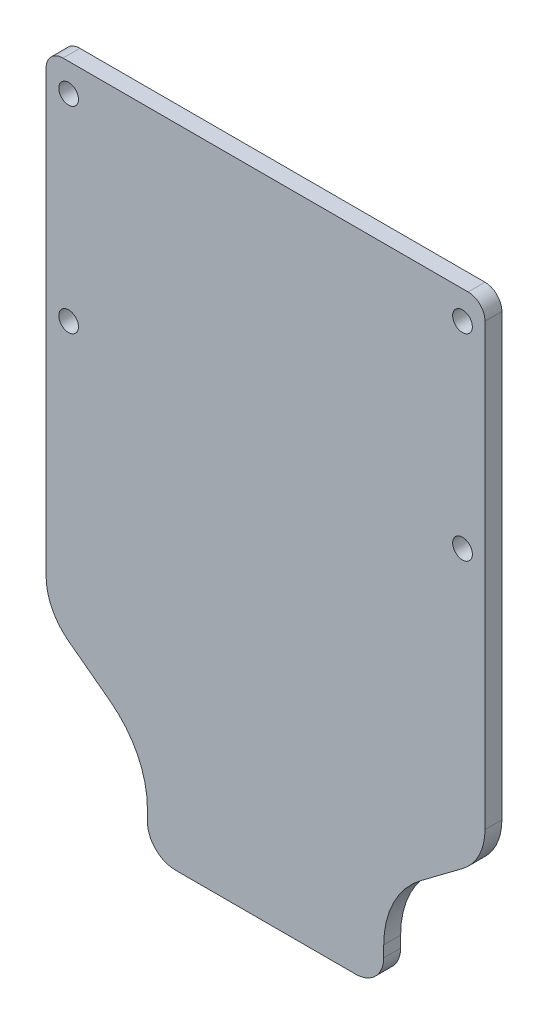
SolidWorks part; units mm, degrees
ref_plane "Front Plane" through (0, 0, 0) normal (0, 0, 1) x (1, 0, 0)
ref_plane "Top Plane" through (0, 0, 0) normal (0, 1, 0) x (1, 0, 0)
ref_plane "Right Plane" through (0, 0, 0) normal (1, 0, 0) x (0, 0, -1)
sketch "Sketch1" plane through (0, 0, 0) normal (0, 0, 1) x (1, 0, 0)
  line L1 (-35, -17.5) -> (35, -17.5) construction
  line L2 (-35, -17.5) -> (-35, 17.5) construction
  line L3 (-35, 17.5) -> (35, 17.5) construction
  line L4 (35, -17.5) -> (35, 17.5) construction
  line L5 (-35, -17.5) -> (35, 17.5) construction
  line L6 (-35, 17.5) -> (35, -17.5) construction
  line L7 (39, -22.5) -> (-39, -22.5)
  line L8 (39, -22.5) -> (39, 22.5)
  line L9 (39, 22.5) -> (-39, 22.5)
  line L10 (-39, -22.5) -> (-39, 22.5)
  line L11 (39, -22.5) -> (-39, 22.5) construction
  line L12 (39, 22.5) -> (-39, -22.5) construction
  circle A0 centre (-35, 17.5) radius 1.75
  circle A1 centre (35, 17.5) radius 1.75
  circle A2 centre (35, -17.5) radius 1.75
  circle A3 centre (-35, -17.5) radius 1.75
  point P0 (0, 0)
  point P10 (0, 0)
  dimension "D3" = 3.5
  dimension "D1" = 70
  dimension "D2" = 35
  dimension "D4" = 78
  dimension "D5" = 45
extrude "Boss-Extrude1" add sketch "Sketch1" along normal blind 3
sketch "Sketch2" plane through (0, -22.5, 0) normal (0, -1, 0) x (1, 0, 0)
  line L4 (-39, 0) -> (39, 0)
  line L5 (39, 0) -> (39, 3)
  line L6 (39, 3) -> (-39, 3)
  line L7 (-39, 3) -> (-39, 0)
  line L8 (-39, 0) -> (39, 0)
  line L9 (39, 0) -> (39, 3)
  line L10 (39, 3) -> (-39, 3)
  line L11 (-39, 3) -> (-39, 0)
  dimension "D1" = 0
extrude "Boss-Extrude2" add sketch "Sketch2" along normal blind 70
sketch "Sketch3" plane through (0, 0, 3) normal (0, 0, 1) x (1, 0, 0)
  line L0 (41, -36.9246) -> (91.4695, -36.9246)
  line L1 (91.4695, -36.9246) -> (78.5429, -118.6496)
  line L2 (78.5429, -118.6496) -> (-67.027, -120.2552)
  line L3 (-67.027, -120.2552) -> (-84.5097, -42.4751)
  line L4 (-84.5097, -42.4751) -> (-81.6554, -36.9246)
  line L5 (-81.6554, -36.9246) -> (-41, -36.9246)
  line L12 (41, -55.5) -> (41, -36.9246)
  line L13 (41, -36.9246) -> (39.1575, -36.9246)
  line L14 (25.5, -28.5324) -> (25.5, 16.1465)
  line L15 (25.5, 16.1465) -> (-25.5, 16.1465)
  line L16 (-25.5, 16.1465) -> (-25.5, -28.5324)
  line L17 (-39.1575, -36.9246) -> (-41, -36.9246)
  line L18 (-41, -36.9246) -> (-41, -55.5)
  line L19 (-35.6, -66.3) -> (-27.6, -72.3)
  line L20 (-21, -85.5) -> (-21, -101)
  line L21 (-15.5, -106.5) -> (15.5, -106.5)
  line L22 (21, -101) -> (21, -85.5)
  line L23 (27.6, -72.3) -> (35.6, -66.3)
  line L24 (41, -55.5) -> (41, -36.9246)
  line L30 (-41, -36.9246) -> (-41, -55.5)
  line L31 (-35.6, -66.3) -> (-27.6, -72.3)
  line L32 (-21, -85.5) -> (-21, -101)
  line L33 (-15.5, -106.5) -> (15.5, -106.5)
  line L34 (21, -101) -> (21, -85.5)
  line L35 (27.6, -72.3) -> (35.6, -66.3)
  arc A6 (35.6, -66.3) -> (41, -55.5) centre (27.5, -55.5) ccw
  arc A7 (-41, -55.5) -> (-35.6, -66.3) centre (-27.5, -55.5) ccw
  arc A8 (-21, -85.5) -> (-27.6, -72.3) centre (-37.5, -85.5) ccw
  arc A9 (-21, -101) -> (-15.5, -106.5) centre (-15.5, -101) ccw
  arc A10 (15.5, -106.5) -> (21, -101) centre (15.5, -101) ccw
  arc A11 (27.6, -72.3) -> (21, -85.5) centre (37.5, -85.5) ccw
  arc A12 (35.6, -66.3) -> (41, -55.5) centre (27.5, -55.5) ccw
  arc A13 (-41, -55.5) -> (-35.6, -66.3) centre (-27.5, -55.5) ccw
  arc A14 (-21, -85.5) -> (-27.6, -72.3) centre (-37.5, -85.5) ccw
  arc A15 (-21, -101) -> (-15.5, -106.5) centre (-15.5, -101) ccw
  arc A16 (15.5, -106.5) -> (21, -101) centre (15.5, -101) ccw
  arc A17 (27.6, -72.3) -> (21, -85.5) centre (37.5, -85.5) ccw
  spline S2 degree 3 poles (238.2417, -1016.9068) (482.9236, 1225.8843) (151.0472, -66.9011) (34.2813, -36.2095) (33.6007, -35.9809) (32.2948, -35.4386) (31.6657, -35.1246) (30.4562, -34.4087) (29.8759, -34.0068) (29.0456, -33.3318) (28.7776, -33.0963) (28.2648, -32.609) (28.019, -32.3566) (27.3139, -31.5726) (26.8865, -31.0146) (26.3128, -30.1217) (26.1325, -29.8141) (25.8807, -29.3405) (25.8, -29.181) (21.788, -20.8359) (23.9853, -2.4289) (374.6838, -965.5474) knots -20.965805 -20.965805 -20.965805 -20.965805 0.25 0.25 0.375 0.375 0.5 0.5 0.625 0.625 0.6875 0.6875 0.75 0.75 0.875 0.875 0.9375 0.9375 0.96875 0.96875 2.556537 2.556537 2.556537 2.556537 only from (39.1575, -36.9246) to (25.5, -28.5324)
  spline S3 degree 3 poles (-374.6958, -965.5804) (-23.9853, -2.4285) (-21.7879, -20.8358) (-25.8, -29.181) (-25.8807, -29.3405) (-26.1325, -29.8141) (-26.3128, -30.1217) (-26.8865, -31.0146) (-27.3139, -31.5726) (-28.019, -32.3566) (-28.2648, -32.609) (-28.7776, -33.0963) (-29.0456, -33.3318) (-29.8759, -34.0068) (-30.4562, -34.4087) (-31.6657, -35.1246) (-32.2948, -35.4386) (-33.6007, -35.9809) (-34.2813, -36.2095) (-151.0471, -66.9011) (-482.9234, 1225.8833) (-238.242, -1016.9042) knots -1.556555 -1.556555 -1.556555 -1.556555 0.03125 0.03125 0.0625 0.0625 0.125 0.125 0.25 0.25 0.3125 0.3125 0.375 0.375 0.5 0.5 0.625 0.625 0.75 0.75 21.965797 21.965797 21.965797 21.965797 only from (-25.5, -28.5324) to (-39.1575, -36.9246)
  dimension "D1" = 0
extrude "Cut-Extrude1" cut sketch "Sketch3" against normal through all
fillet "Fillet1" radius 5 2 edges at (21, -92.5, 1.5) (-21, -92.5, 1.5)
fillet "Fillet2" radius 10 2 edges at (39, -62.5711, 1.5) (-39, -62.5711, 1.5)
fillet "Fillet3" radius 3 2 edges at (39, 22.5, 1.5) (-39, 22.5, 1.5)
